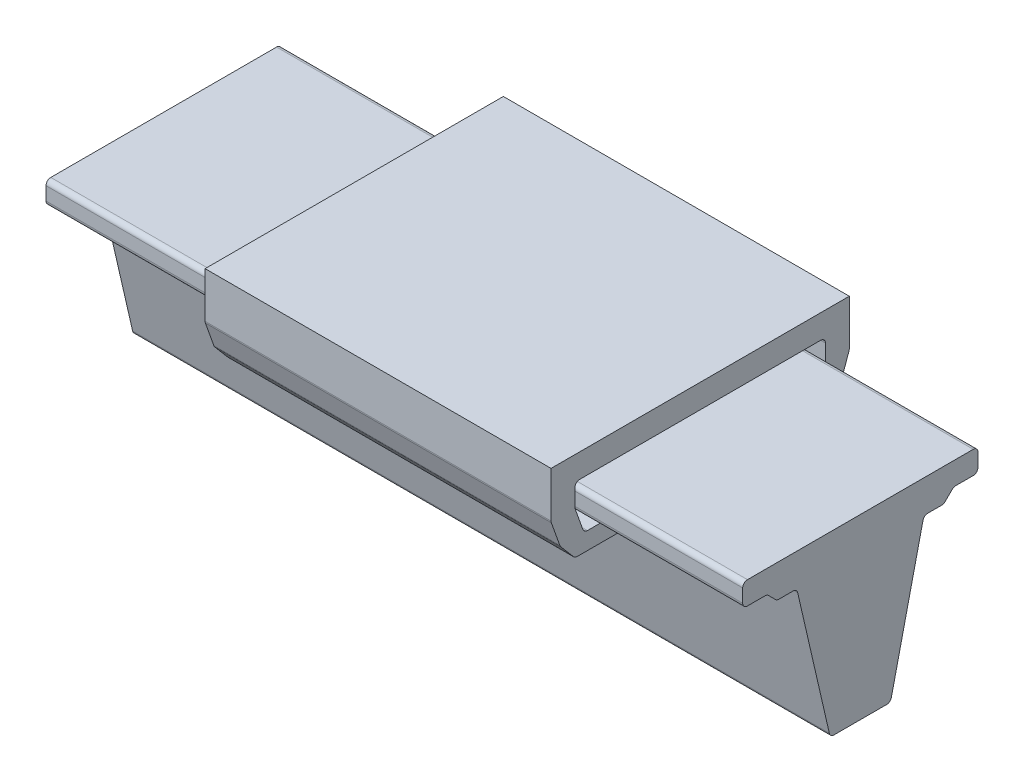
SolidWorks part; units mm, degrees
ref_plane "Front Plane" through (0, 0, 0) normal (0, 0, 1) x (1, 0, 0)
ref_plane "Top Plane" through (0, 0, 0) normal (0, 1, 0) x (1, 0, 0)
ref_plane "Right Plane" through (0, 0, 0) normal (1, 0, 0) x (0, 0, -1)
sketch "Sketch2" plane through (0, 0, 0) normal (1, 0, 0) x (0, 0, -1)
  line L0 (0.2316, -19.5618) -> (7.3931, -39.6822)
  line L1 (24, 0) -> (226.0039, 0)
  line L2 (0, 0) -> (0, 20)
  line L3 (0, 20) -> (250, 20)
  line L4 (250, 0) -> (250, 20)
  line L6 (0, 0) -> (0, -18.2205)
  line L8 (20, -4) -> (20, -18.2205)
  line L9 (250, 0) -> (250.0039, 0)
  line L10 (20.2316, -19.5618) -> (26.6924, -37.7137)
  line L11 (30.4608, -40.3724) -> (47.6513, -40.3724)
  line L12 (125.002, 0) -> (115.1335, 0)
  line L13 (47.6513, -54.9225) -> (21.8504, -54.9225)
  line L14 (18.802, -53.5123) -> (8.1131, -40.9308)
  line L15 (47.6513, -40.3724) -> (65.1126, -40.3724)
  line L16 (69.1126, -44.3724) -> (69.1126, -50.9225)
  line L17 (65.1126, -54.9225) -> (47.6513, -54.9225)
  line L18 (49.2331, -30.355) -> (55.1704, -36.2922)
  line L19 (250.0039, 0) -> (250.0039, -18.2014)
  line L20 (230.0039, -4) -> (230.0039, -18.2014)
  line L21 (184.8914, -54.9033) -> (202.3527, -54.9033)
  line L22 (180.8914, -44.3533) -> (180.8914, -50.9033)
  line L23 (202.3527, -40.3533) -> (184.8914, -40.3533)
  line L24 (231.202, -53.4932) -> (241.8909, -40.9116)
  line L25 (202.3527, -54.9033) -> (228.1536, -54.9033)
  line L26 (219.5431, -40.3533) -> (202.3527, -40.3533)
  line L27 (229.7724, -19.5427) -> (223.3115, -37.6946)
  line L28 (249.7724, -19.5427) -> (242.6109, -39.6631)
  line L29 (31.6374, -29.1834) -> (46.4047, -29.1834)
  line L30 (27.6374, -25.1834) -> (27.6374, -14.0964)
  line L31 (31.6374, -10.0964) -> (220.8835, -10.0964)
  line L32 (224.8835, -25.1834) -> (224.8835, -14.0964)
  line L33 (57.9988, -37.4638) -> (69.824, -37.4638)
  line L34 (73.7221, -40.5668) -> (100.2819, -155.9878)
  line L35 (206.1162, -10.0964) -> (206.1162, -29.1834)
  line L36 (178.7988, -40.5668) -> (152.239, -155.9878)
  line L37 (148.3409, -159.0908) -> (104.18, -159.0908)
  line L38 (203.2878, -30.355) -> (197.3505, -36.2922)
  line L39 (194.5221, -37.4638) -> (182.6969, -37.4638)
  line L40 (206.1162, -29.1834) -> (220.8835, -29.1834)
  line L42 (46.4047, -10.0964) -> (46.4047, -29.1834)
  line L43 (20, -10.0964) -> (9.9072, -10.0964)
  line L45 (20, -10.0964) -> (20, -29.1834)
  line L46 (20, -29.1834) -> (9.9072, -29.1834)
  line L47 (9.9072, -10.0964) -> (9.9072, -29.1834)
  line L48 (230.0039, -11.1007) -> (240.71, -11.1007)
  line L49 (230.0039, -11.1007) -> (230.0039, -29.1834)
  line L50 (230.0039, -29.1834) -> (240.71, -29.1834)
  line L51 (240.71, -11.1007) -> (240.71, -29.1834)
  line L52 (47.6513, -40.3724) -> (65.1126, -40.3724)
  line L53 (47.6513, -40.3724) -> (47.6513, -47.6474)
  line L54 (47.6513, -47.6474) -> (69.1126, -47.6474)
  line L55 (69.1126, -44.3724) -> (69.1126, -47.6474)
  line L56 (202.3527, -40.3533) -> (184.8914, -40.3533)
  line L57 (202.3527, -40.3533) -> (202.3527, -47.6283)
  line L58 (202.3527, -47.6283) -> (180.8914, -47.6283)
  line L59 (180.8914, -44.3533) -> (180.8914, -47.6283)
  arc A0 (31.6374, -29.1834) -> (27.6374, -25.1834) centre (31.6374, -25.1834) cw
  arc A1 (27.6374, -14.0964) -> (31.6374, -10.0964) centre (31.6374, -14.0964) cw
  arc A2 (220.8835, -10.0964) -> (224.8835, -14.0964) centre (220.8835, -14.0964) cw
  arc A3 (220.8835, -29.1834) -> (224.8835, -25.1834) centre (220.8835, -25.1834) ccw
  arc A4 (55.1704, -36.2922) -> (57.9988, -37.4638) centre (57.9988, -33.4638) ccw
  arc A5 (49.2331, -30.355) -> (46.4047, -29.1834) centre (46.4047, -33.1834) ccw
  arc A6 (203.2878, -30.355) -> (206.1162, -29.1834) centre (206.1162, -33.1834) cw
  arc A7 (197.3505, -36.2922) -> (194.5221, -37.4638) centre (194.5221, -33.4638) cw
  arc A8 (178.7988, -40.5668) -> (182.6969, -37.4638) centre (182.6969, -41.4638) cw
  arc A9 (24, 0) -> (20, -4) centre (24, -4) ccw
  arc A10 (226.0039, 0) -> (230.0039, -4) centre (226.0039, -4) cw
  arc A11 (230.0039, -18.2014) -> (229.7724, -19.5427) centre (226.0039, -18.2014) cw
  arc A12 (69.1126, -50.9225) -> (65.1126, -54.9225) centre (65.1126, -50.9225) cw
  arc A13 (65.1126, -40.3724) -> (69.1126, -44.3724) centre (65.1126, -44.3724) cw
  arc A14 (20.2316, -19.5618) -> (20, -18.2205) centre (24, -18.2205) cw
  arc A15 (26.6924, -37.7137) -> (30.4608, -40.3724) centre (30.4608, -36.3724) ccw
  arc A16 (0.2316, -19.5618) -> (0, -18.2205) centre (4, -18.2205) cw
  arc A17 (7.3931, -39.6822) -> (8.1131, -40.9308) centre (11.1615, -38.3409) ccw
  arc A18 (21.8504, -54.9225) -> (18.802, -53.5123) centre (21.8504, -50.9225) cw
  arc A19 (250.0039, -18.2014) -> (249.7724, -19.5427) centre (246.0039, -18.2014) cw
  arc A20 (241.8909, -40.9116) -> (242.6109, -39.6631) centre (238.8424, -38.3218) ccw
  arc A21 (231.202, -53.4932) -> (228.1536, -54.9033) centre (228.1536, -50.9033) cw
  arc A22 (219.5431, -40.3533) -> (223.3115, -37.6946) centre (219.5431, -36.3533) ccw
  arc A23 (180.8914, -44.3533) -> (184.8914, -40.3533) centre (184.8914, -44.3533) cw
  arc A24 (184.8914, -54.9033) -> (180.8914, -50.9033) centre (184.8914, -50.9033) cw
  arc A25 (152.239, -155.9878) -> (148.3409, -159.0908) centre (148.3409, -155.0908) cw
  arc A26 (100.2819, -155.9878) -> (104.18, -159.0908) centre (104.18, -155.0908) ccw
  arc A27 (69.824, -37.4638) -> (73.7221, -40.5668) centre (69.824, -41.4638) cw
  arc A28 (184.8914, -40.3533) -> (180.8914, -44.3533) centre (184.8914, -44.3533) ccw
  arc A29 (65.1126, -40.3724) -> (69.1126, -44.3724) centre (65.1126, -44.3724) cw
  dimension "D1" = 4
  dimension "D2" = 4
  dimension "D3" = 4
  dimension "D4" = 4
  dimension "D5" = 4
  dimension "D6" = 4
  dimension "D7" = 4
  dimension "D8" = 4
  dimension "D9" = 4
  dimension "D10" = 4
  dimension "D11" = 4
  dimension "D12" = 4
extrude "Boss-Extrude5" add sketch "Sketch2" along normal blind 290 contours A13 L15 L53 L54 L16 | L43 L47 L46 L45 L8 | A23 L22 L58 L57 L23 | L51 L48 L20 L49 L50 | L40 A3 L32 A2 L31 L35 | A1 L30 A0 L29 L42 L31 | L33 A27 L34 A26 L37 A25 L36 A8 L39 A7 L38 A6 L35 L31 L42 A5 L18 A4 | A24 L21 L25 A21 L24 A20 L28 A19 L19 L9 L4 L3 L2 L6 A16 L0 A17 L14 A18 L13 L17 A12 L16 L54 L53 L11 A15 L10 A14 L45 L46 L47 L43 L8 A9 L1 A10 L20 L48 L51 L50 L49 A11 L27 A22 L26 L57 L58 L22
sketch "Sketch3" plane through (290, 0, 0) normal (1, 0, 0) x (0, 0, -1)
  line L12 (206.1162, -29.1834) -> (220.8835, -29.1834)
  line L13 (224.8835, -25.1834) -> (224.8835, -14.0964)
  line L14 (220.8835, -10.0964) -> (31.6374, -10.0964)
  line L15 (27.6374, -14.0964) -> (27.6374, -25.1834)
  line L16 (31.6374, -29.1834) -> (46.4047, -29.1834)
  line L17 (49.2331, -30.355) -> (55.1704, -36.2922)
  line L18 (57.9988, -37.4638) -> (69.824, -37.4638)
  line L19 (73.7221, -40.5668) -> (100.2819, -155.9878)
  line L20 (104.18, -159.0908) -> (148.3409, -159.0908)
  line L21 (152.239, -155.9878) -> (178.7988, -40.5668)
  line L22 (182.6969, -37.4638) -> (194.5221, -37.4638)
  line L23 (197.3505, -36.2922) -> (203.2878, -30.355)
  line L24 (206.1162, -29.1834) -> (220.8835, -29.1834)
  line L25 (224.8835, -25.1834) -> (224.8835, -14.0964)
  line L26 (220.8835, -10.0964) -> (31.6374, -10.0964)
  line L27 (27.6374, -14.0964) -> (27.6374, -25.1834)
  line L28 (31.6374, -29.1834) -> (46.4047, -29.1834)
  line L29 (49.2331, -30.355) -> (55.1704, -36.2922)
  line L30 (57.9988, -37.4638) -> (69.824, -37.4638)
  line L31 (73.7221, -40.5668) -> (100.2819, -155.9878)
  line L32 (104.18, -159.0908) -> (148.3409, -159.0908)
  line L33 (152.239, -155.9878) -> (178.7988, -40.5668)
  line L34 (182.6969, -37.4638) -> (194.5221, -37.4638)
  line L35 (197.3505, -36.2922) -> (203.2878, -30.355)
  arc A12 (220.8835, -29.1834) -> (224.8835, -25.1834) centre (220.8835, -25.1834) ccw
  arc A13 (224.8835, -14.0964) -> (220.8835, -10.0964) centre (220.8835, -14.0964) ccw
  arc A14 (31.6374, -10.0964) -> (27.6374, -14.0964) centre (31.6374, -14.0964) ccw
  arc A15 (27.6374, -25.1834) -> (31.6374, -29.1834) centre (31.6374, -25.1834) ccw
  arc A16 (49.2331, -30.355) -> (46.4047, -29.1834) centre (46.4047, -33.1834) ccw
  arc A17 (55.1704, -36.2922) -> (57.9988, -37.4638) centre (57.9988, -33.4638) ccw
  arc A18 (73.7221, -40.5668) -> (69.824, -37.4638) centre (69.824, -41.4638) ccw
  arc A19 (100.2819, -155.9878) -> (104.18, -159.0908) centre (104.18, -155.0908) ccw
  arc A20 (148.3409, -159.0908) -> (152.239, -155.9878) centre (148.3409, -155.0908) ccw
  arc A21 (182.6969, -37.4638) -> (178.7988, -40.5668) centre (182.6969, -41.4638) ccw
  arc A22 (194.5221, -37.4638) -> (197.3505, -36.2922) centre (194.5221, -33.4638) ccw
  arc A23 (206.1162, -29.1834) -> (203.2878, -30.355) centre (206.1162, -33.1834) ccw
  arc A24 (220.8835, -29.1834) -> (224.8835, -25.1834) centre (220.8835, -25.1834) ccw
  arc A25 (224.8835, -14.0964) -> (220.8835, -10.0964) centre (220.8835, -14.0964) ccw
  arc A26 (31.6374, -10.0964) -> (27.6374, -14.0964) centre (31.6374, -14.0964) ccw
  arc A27 (27.6374, -25.1834) -> (31.6374, -29.1834) centre (31.6374, -25.1834) ccw
  arc A28 (49.2331, -30.355) -> (46.4047, -29.1834) centre (46.4047, -33.1834) ccw
  arc A29 (55.1704, -36.2922) -> (57.9988, -37.4638) centre (57.9988, -33.4638) ccw
  arc A30 (73.7221, -40.5668) -> (69.824, -37.4638) centre (69.824, -41.4638) ccw
  arc A31 (100.2819, -155.9878) -> (104.18, -159.0908) centre (104.18, -155.0908) ccw
  arc A32 (148.3409, -159.0908) -> (152.239, -155.9878) centre (148.3409, -155.0908) ccw
  arc A33 (182.6969, -37.4638) -> (178.7988, -40.5668) centre (182.6969, -41.4638) ccw
  arc A34 (194.5221, -37.4638) -> (197.3505, -36.2922) centre (194.5221, -33.4638) ccw
  arc A35 (206.1162, -29.1834) -> (203.2878, -30.355) centre (206.1162, -33.1834) ccw
  dimension "D1" = 0
extrude "Boss-Extrude6" add sketch "Sketch3" along normal blind 133
sketch "Sketch4" plane through (0, 0, 0) normal (-1, 0, 0) x (0, 0, 1)
  line L12 (-220.8835, -29.1834) -> (-206.1162, -29.1834)
  line L13 (-203.2878, -30.355) -> (-197.3505, -36.2922)
  line L14 (-194.5221, -37.4638) -> (-182.6969, -37.4638)
  line L15 (-178.7988, -40.5668) -> (-152.239, -155.9878)
  line L16 (-148.3409, -159.0908) -> (-104.18, -159.0908)
  line L17 (-100.2819, -155.9878) -> (-73.7221, -40.5668)
  line L18 (-69.824, -37.4638) -> (-57.9988, -37.4638)
  line L19 (-55.1704, -36.2922) -> (-49.2331, -30.355)
  line L20 (-46.4047, -29.1834) -> (-31.6374, -29.1834)
  line L21 (-27.6374, -25.1834) -> (-27.6374, -14.0964)
  line L22 (-31.6374, -10.0964) -> (-220.8835, -10.0964)
  line L23 (-224.8835, -14.0964) -> (-224.8835, -25.1834)
  line L24 (-220.8835, -29.1834) -> (-206.1162, -29.1834)
  line L25 (-203.2878, -30.355) -> (-197.3505, -36.2922)
  line L26 (-194.5221, -37.4638) -> (-182.6969, -37.4638)
  line L27 (-178.7988, -40.5668) -> (-152.239, -155.9878)
  line L28 (-148.3409, -159.0908) -> (-104.18, -159.0908)
  line L29 (-100.2819, -155.9878) -> (-73.7221, -40.5668)
  line L30 (-69.824, -37.4638) -> (-57.9988, -37.4638)
  line L31 (-55.1704, -36.2922) -> (-49.2331, -30.355)
  line L32 (-46.4047, -29.1834) -> (-31.6374, -29.1834)
  line L33 (-27.6374, -25.1834) -> (-27.6374, -14.0964)
  line L34 (-31.6374, -10.0964) -> (-220.8835, -10.0964)
  line L35 (-224.8835, -14.0964) -> (-224.8835, -25.1834)
  arc A12 (-203.2878, -30.355) -> (-206.1162, -29.1834) centre (-206.1162, -33.1834) ccw
  arc A13 (-197.3505, -36.2922) -> (-194.5221, -37.4638) centre (-194.5221, -33.4638) ccw
  arc A14 (-178.7988, -40.5668) -> (-182.6969, -37.4638) centre (-182.6969, -41.4638) ccw
  arc A15 (-152.239, -155.9878) -> (-148.3409, -159.0908) centre (-148.3409, -155.0908) ccw
  arc A16 (-104.18, -159.0908) -> (-100.2819, -155.9878) centre (-104.18, -155.0908) ccw
  arc A17 (-69.824, -37.4638) -> (-73.7221, -40.5668) centre (-69.824, -41.4638) ccw
  arc A18 (-57.9988, -37.4638) -> (-55.1704, -36.2922) centre (-57.9988, -33.4638) ccw
  arc A19 (-46.4047, -29.1834) -> (-49.2331, -30.355) centre (-46.4047, -33.1834) ccw
  arc A20 (-31.6374, -29.1834) -> (-27.6374, -25.1834) centre (-31.6374, -25.1834) ccw
  arc A21 (-27.6374, -14.0964) -> (-31.6374, -10.0964) centre (-31.6374, -14.0964) ccw
  arc A22 (-220.8835, -10.0964) -> (-224.8835, -14.0964) centre (-220.8835, -14.0964) ccw
  arc A23 (-224.8835, -25.1834) -> (-220.8835, -29.1834) centre (-220.8835, -25.1834) ccw
  arc A24 (-203.2878, -30.355) -> (-206.1162, -29.1834) centre (-206.1162, -33.1834) ccw
  arc A25 (-197.3505, -36.2922) -> (-194.5221, -37.4638) centre (-194.5221, -33.4638) ccw
  arc A26 (-178.7988, -40.5668) -> (-182.6969, -37.4638) centre (-182.6969, -41.4638) ccw
  arc A27 (-152.239, -155.9878) -> (-148.3409, -159.0908) centre (-148.3409, -155.0908) ccw
  arc A28 (-104.18, -159.0908) -> (-100.2819, -155.9878) centre (-104.18, -155.0908) ccw
  arc A29 (-69.824, -37.4638) -> (-73.7221, -40.5668) centre (-69.824, -41.4638) ccw
  arc A30 (-57.9988, -37.4638) -> (-55.1704, -36.2922) centre (-57.9988, -33.4638) ccw
  arc A31 (-46.4047, -29.1834) -> (-49.2331, -30.355) centre (-46.4047, -33.1834) ccw
  arc A32 (-31.6374, -29.1834) -> (-27.6374, -25.1834) centre (-31.6374, -25.1834) ccw
  arc A33 (-27.6374, -14.0964) -> (-31.6374, -10.0964) centre (-31.6374, -14.0964) ccw
  arc A34 (-220.8835, -10.0964) -> (-224.8835, -14.0964) centre (-220.8835, -14.0964) ccw
  arc A35 (-224.8835, -25.1834) -> (-220.8835, -29.1834) centre (-220.8835, -25.1834) ccw
  dimension "D1" = 0
extrude "Boss-Extrude7" add sketch "Sketch4" along normal blind 161
sketch "Sketch5" plane through (0, 0, 0) normal (-1, 0, 0) x (0, 0, 1)
  line L20 (-20.2316, -19.5618) -> (-26.6924, -37.7137)
  line L21 (-30.4608, -40.3724) -> (-65.1126, -40.3724)
  line L22 (-69.1126, -44.3724) -> (-69.1126, -50.9225)
  line L23 (-65.1126, -54.9225) -> (-21.8504, -54.9225)
  line L24 (-18.802, -53.5123) -> (-8.1131, -40.9308)
  line L25 (-7.3931, -39.6822) -> (-0.2316, -19.5618)
  line L26 (0, -18.2205) -> (0, 20)
  line L27 (0, 20) -> (-250, 20)
  line L28 (-250, 20) -> (-250, 0)
  line L29 (-250, 0) -> (-250.0039, 0)
  line L30 (-250.0039, 0) -> (-250.0039, -18.2014)
  line L31 (-249.7724, -19.5427) -> (-242.6109, -39.6631)
  line L32 (-241.8909, -40.9116) -> (-231.202, -53.4932)
  line L33 (-228.1536, -54.9033) -> (-184.8914, -54.9033)
  line L34 (-180.8914, -50.9033) -> (-180.8914, -44.3533)
  line L35 (-184.8914, -40.3533) -> (-219.5431, -40.3533)
  line L36 (-223.3115, -37.6946) -> (-229.7724, -19.5427)
  line L37 (-230.0039, -18.2014) -> (-230.0039, -4)
  line L38 (-226.0039, 0) -> (-24, 0)
  line L39 (-20, -4) -> (-20, -18.2205)
  line L40 (-20.2316, -19.5618) -> (-26.6924, -37.7137)
  line L41 (-30.4608, -40.3724) -> (-65.1126, -40.3724)
  line L42 (-69.1126, -44.3724) -> (-69.1126, -50.9225)
  line L43 (-65.1126, -54.9225) -> (-21.8504, -54.9225)
  line L44 (-18.802, -53.5123) -> (-8.1131, -40.9308)
  line L45 (-7.3931, -39.6822) -> (-0.2316, -19.5618)
  line L46 (0, -18.2205) -> (0, 20)
  line L47 (0, 20) -> (-250, 20)
  line L48 (-250, 20) -> (-250, 0)
  line L49 (-250, 0) -> (-250.0039, 0)
  line L50 (-250.0039, 0) -> (-250.0039, -18.2014)
  line L51 (-249.7724, -19.5427) -> (-242.6109, -39.6631)
  line L52 (-241.8909, -40.9116) -> (-231.202, -53.4932)
  line L53 (-228.1536, -54.9033) -> (-184.8914, -54.9033)
  line L54 (-180.8914, -50.9033) -> (-180.8914, -44.3533)
  line L55 (-184.8914, -40.3533) -> (-219.5431, -40.3533)
  line L56 (-223.3115, -37.6946) -> (-229.7724, -19.5427)
  line L57 (-230.0039, -18.2014) -> (-230.0039, -4)
  line L58 (-226.0039, 0) -> (-24, 0)
  line L59 (-20, -4) -> (-20, -18.2205)
  arc A16 (-20.2316, -19.5618) -> (-20, -18.2205) centre (-24, -18.2205) ccw
  arc A17 (-30.4608, -40.3724) -> (-26.6924, -37.7137) centre (-30.4608, -36.3724) ccw
  arc A18 (-65.1126, -40.3724) -> (-69.1126, -44.3724) centre (-65.1126, -44.3724) ccw
  arc A19 (-69.1126, -50.9225) -> (-65.1126, -54.9225) centre (-65.1126, -50.9225) ccw
  arc A20 (-21.8504, -54.9225) -> (-18.802, -53.5123) centre (-21.8504, -50.9225) ccw
  arc A21 (-8.1131, -40.9308) -> (-7.3931, -39.6822) centre (-11.1615, -38.3409) ccw
  arc A22 (-0.2316, -19.5618) -> (0, -18.2205) centre (-4, -18.2205) ccw
  arc A23 (-250.0039, -18.2014) -> (-249.7724, -19.5427) centre (-246.0039, -18.2014) ccw
  arc A24 (-242.6109, -39.6631) -> (-241.8909, -40.9116) centre (-238.8424, -38.3218) ccw
  arc A25 (-231.202, -53.4932) -> (-228.1536, -54.9033) centre (-228.1536, -50.9033) ccw
  arc A26 (-184.8914, -54.9033) -> (-180.8914, -50.9033) centre (-184.8914, -50.9033) ccw
  arc A27 (-180.8914, -44.3533) -> (-184.8914, -40.3533) centre (-184.8914, -44.3533) ccw
  arc A28 (-223.3115, -37.6946) -> (-219.5431, -40.3533) centre (-219.5431, -36.3533) ccw
  arc A29 (-230.0039, -18.2014) -> (-229.7724, -19.5427) centre (-226.0039, -18.2014) ccw
  arc A30 (-226.0039, 0) -> (-230.0039, -4) centre (-226.0039, -4) ccw
  arc A31 (-20, -4) -> (-24, 0) centre (-24, -4) ccw
  arc A32 (-20.2316, -19.5618) -> (-20, -18.2205) centre (-24, -18.2205) ccw
  arc A33 (-30.4608, -40.3724) -> (-26.6924, -37.7137) centre (-30.4608, -36.3724) ccw
  arc A34 (-65.1126, -40.3724) -> (-69.1126, -44.3724) centre (-65.1126, -44.3724) ccw
  arc A35 (-69.1126, -50.9225) -> (-65.1126, -54.9225) centre (-65.1126, -50.9225) ccw
  arc A36 (-21.8504, -54.9225) -> (-18.802, -53.5123) centre (-21.8504, -50.9225) ccw
  arc A37 (-8.1131, -40.9308) -> (-7.3931, -39.6822) centre (-11.1615, -38.3409) ccw
  arc A38 (-0.2316, -19.5618) -> (0, -18.2205) centre (-4, -18.2205) ccw
  arc A39 (-250.0039, -18.2014) -> (-249.7724, -19.5427) centre (-246.0039, -18.2014) ccw
  arc A40 (-242.6109, -39.6631) -> (-241.8909, -40.9116) centre (-238.8424, -38.3218) ccw
  arc A41 (-231.202, -53.4932) -> (-228.1536, -54.9033) centre (-228.1536, -50.9033) ccw
  arc A42 (-184.8914, -54.9033) -> (-180.8914, -50.9033) centre (-184.8914, -50.9033) ccw
  arc A43 (-180.8914, -44.3533) -> (-184.8914, -40.3533) centre (-184.8914, -44.3533) ccw
  arc A44 (-223.3115, -37.6946) -> (-219.5431, -40.3533) centre (-219.5431, -36.3533) ccw
  arc A45 (-230.0039, -18.2014) -> (-229.7724, -19.5427) centre (-226.0039, -18.2014) ccw
  arc A46 (-226.0039, 0) -> (-230.0039, -4) centre (-226.0039, -4) ccw
  arc A47 (-20, -4) -> (-24, 0) centre (-24, -4) ccw
  dimension "D1" = 0
